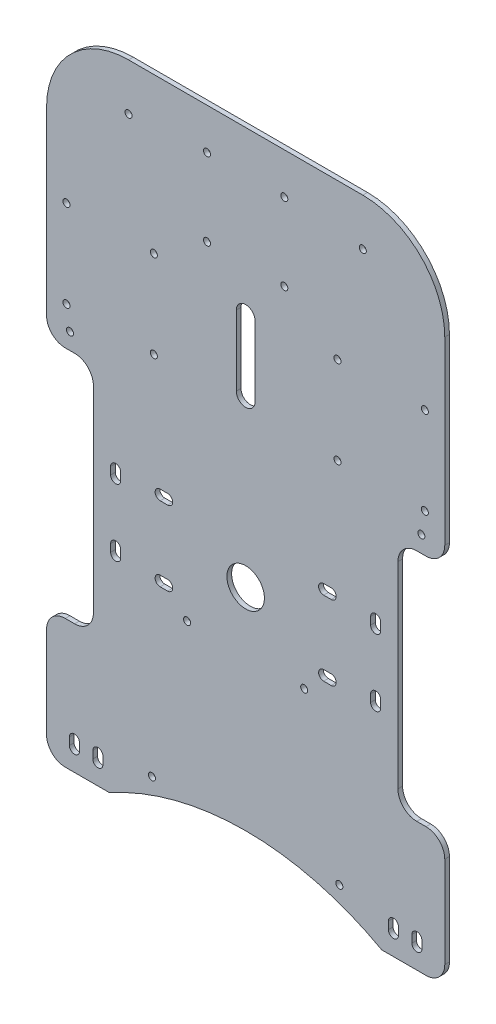
SolidWorks part; units mm, degrees
ref_plane "Front Plane" through (0, 0, 0) normal (0, 0, 1) x (1, 0, 0)
ref_plane "Top Plane" through (0, 0, 0) normal (0, 1, 0) x (1, 0, 0)
ref_plane "Right Plane" through (0, 0, 0) normal (1, 0, 0) x (0, 0, -1)
sketch "Sketch1" plane through (0, 0, 0) normal (0, 0, 1) x (1, 0, 0)
  line L0 (0, 234.6428) -> (0, -211.6883) construction
  line L1 (-148.3119, 0) -> (158.122, 0) construction
  line L2 (85, 170) -> (-85, 170)
  line L3 (-85, 170) -> (-85, 50)
  line L4 (-85, 50) -> (-65, 50)
  line L5 (-65, 50) -> (-65, -50)
  line L6 (-65, -50) -> (-85, -50)
  line L7 (-85, -50) -> (-85, -105)
  line L8 (-85, -105) -> (-58.0948, -105)
  line L9 (85, -50) -> (85, -105)
  line L10 (65, -50) -> (85, -50)
  line L11 (65, 50) -> (65, -50)
  line L12 (85, 50) -> (65, 50)
  line L13 (85, 170) -> (85, 50)
  line L14 (-183.5211, -105) -> (209.6702, -105) construction
  line L15 (-183.5211, -210) -> (209.6702, -210) construction
  line L16 (58.0948, -105) -> (85, -105)
  arc A0 (58.0948, -105) -> (-58.0948, -105) centre (0, -210) ccw
  circle A1 centre (0, 0) radius 8
  point P15 (0, -124.5914)
  point P20 (0, 170)
  dimension "D8" = 120
  dimension "D9" = 16
  dimension "D1" = 100
  dimension "D2" = 50
  dimension "D3" = 20
  dimension "D4" = 120
  dimension "D5" = 55
  dimension "D6" = 85
  dimension "D10" = 85
  dimension "D7" = 105
extrude "Boss-Extrude1" add sketch "Sketch1" along normal blind 2
fillet "Fillet3" radius 35 2 edges at (-85, 170, 1) (85, 170, 1)
fillet "Fillet4" radius 8 5 edges at (-65, -50, 1) (-85, -50, 1) (-85, -105, 1) (-85, 50, 1) (-65, 50, 1)
fillet "Fillet5" radius 8 5 edges at (65, -50, 1) (85, -50, 1) (85, -105, 1) (65, 50, 1) (85, 50, 1)
sketch "Sketch6" plane through (0, 0, 2) normal (0, 0, 1) x (1, 0, 0)
  line L0 (0, 177.7315) -> (0, -125.1538) construction
  line L1 (-144.5008, 0) -> (190.5364, 0) construction
  line L2 (-85, 180.289) -> (-85, -129.9035) construction
  line L3 (-78, 180.289) -> (-78, -129.9035) construction
  line L4 (-144.5008, 50) -> (190.5364, 50) construction
  line L5 (-144.5008, 65) -> (190.5364, 65) construction
  line L6 (-76.5, 180.289) -> (-76.5, -129.9035) construction
  line L7 (-144.5008, 66.5) -> (190.5364, 66.5) construction
  line L8 (-144.5008, 103.8) -> (190.5364, 103.8) construction
  line L9 (-39.2, 180.289) -> (-39.2, -129.9035) construction
  circle A0 centre (-76.5, 66.5) radius 1.5
  circle A1 centre (-76.5, 103.8) radius 1.5
  circle A2 centre (-39.2, 103.8) radius 1.5
  circle A3 centre (-39.2, 66.5) radius 1.5
  circle A4 centre (76.5, 66.5) radius 1.5
  circle A5 centre (76.5, 103.8) radius 1.5
  circle A6 centre (39.2, 103.8) radius 1.5
  circle A7 centre (39.2, 66.5) radius 1.5
  dimension "D7" = 37.3
  dimension "D1" = 7
  dimension "D2" = 50
  dimension "D3" = 15
  dimension "D4" = 1.5
  dimension "D5" = 1.5
  dimension "D6" = 37.3
extrude "Cut-Extrude1" cut sketch "Sketch6" against normal blind 2
sketch "Sketch8" plane through (0, 0, 0) normal (0, 0, -1) x (-1, 0, 0)
  line L0 (0, 179.0295) -> (0, -122.4445) construction
  line L1 (-76.5, 66.5) -> (-76.5, 103.8) construction
  line L2 (-97.6433, 85.5254) -> (107.9764, 85.5254) construction
  line L3 (0, 70.5254) -> (0, 100.5254) construction
  line L4 (-4, 70.5254) -> (-4, 100.5254)
  line L5 (4, 70.5254) -> (4, 100.5254)
  line L6 (-133.0869, 0) -> (148.961, 0) construction
  line L8 (-133.0869, -20.65) -> (148.961, -20.65) construction
  line L9 (-133.0869, 20.65) -> (148.961, 20.65) construction
  line L12 (-30, -42) -> (-30, 42)
  line L13 (-30, -42) -> (-30, 42) construction
  line L14 (-36.5, -42) -> (-36.5, 42) construction
  line L15 (-55.5, -42) -> (-55.5, 42)
  line L16 (-55.5, -42) -> (-55.5, 42) construction
  line L17 (-133.0869, -12.7) -> (148.961, -12.7) construction
  line L18 (-133.0869, 12.7) -> (148.961, 12.7) construction
  line L19 (-133.0869, 15.9) -> (148.961, 15.9) construction
  line L20 (-133.0869, -15.9) -> (148.961, -15.9) construction
  line L21 (-33.3, -42) -> (-33.3, 42) construction
  line L22 (-55.5, 15.9) -> (-55.5, 12.7) construction
  line L23 (-53.35, 15.9) -> (-53.35, 12.7)
  line L24 (-57.65, 15.9) -> (-57.65, 12.7)
  line L25 (-55.5, -15.9) -> (-55.5, -12.7) construction
  line L26 (-53.35, -15.9) -> (-53.35, -12.7)
  line L27 (-57.65, -15.9) -> (-57.65, -12.7)
  line L28 (-33.3, 15.9) -> (-36.5, 15.9) construction
  line L29 (-33.3, 13.75) -> (-36.5, 13.75)
  line L30 (-33.3, 18.05) -> (-36.5, 18.05)
  line L31 (-33.3, -15.9) -> (-36.5, -15.9) construction
  line L32 (-33.3, -13.75) -> (-36.5, -13.75)
  line L33 (-33.3, -18.05) -> (-36.5, -18.05)
  line L34 (33.3, -15.9) -> (36.5, -15.9) construction
  line L35 (33.3, -13.75) -> (36.5, -13.75)
  line L36 (33.3, -18.05) -> (36.5, -18.05)
  line L37 (33.3, 15.9) -> (36.5, 15.9) construction
  line L38 (33.3, 13.75) -> (36.5, 13.75)
  line L39 (33.3, 18.05) -> (36.5, 18.05)
  line L40 (55.5, 15.9) -> (55.5, 12.7) construction
  line L41 (53.35, 15.9) -> (53.35, 12.7)
  line L42 (57.65, 15.9) -> (57.65, 12.7)
  line L43 (55.5, -15.9) -> (55.5, -12.7) construction
  line L44 (53.35, -15.9) -> (53.35, -12.7)
  line L45 (57.65, -15.9) -> (57.65, -12.7)
  arc A0 (-4, 70.5254) -> (4, 70.5254) centre (0, 70.5254) ccw
  arc A1 (4, 100.5254) -> (-4, 100.5254) centre (0, 100.5254) ccw
  arc A2 (-53.35, 15.9) -> (-57.65, 15.9) centre (-55.5, 15.9) ccw
  arc A3 (-57.65, 12.7) -> (-53.35, 12.7) centre (-55.5, 12.7) ccw
  arc A4 (-53.35, -15.9) -> (-57.65, -15.9) centre (-55.5, -15.9) cw
  arc A5 (-57.65, -12.7) -> (-53.35, -12.7) centre (-55.5, -12.7) cw
  arc A6 (-33.3, 13.75) -> (-33.3, 18.05) centre (-33.3, 15.9) ccw
  arc A7 (-36.5, 18.05) -> (-36.5, 13.75) centre (-36.5, 15.9) ccw
  arc A8 (-33.3, -13.75) -> (-33.3, -18.05) centre (-33.3, -15.9) cw
  arc A9 (-36.5, -18.05) -> (-36.5, -13.75) centre (-36.5, -15.9) cw
  arc A10 (33.3, -13.75) -> (33.3, -18.05) centre (33.3, -15.9) ccw
  arc A11 (36.5, -18.05) -> (36.5, -13.75) centre (36.5, -15.9) ccw
  arc A12 (33.3, 13.75) -> (33.3, 18.05) centre (33.3, 15.9) cw
  arc A13 (36.5, 18.05) -> (36.5, 13.75) centre (36.5, 15.9) cw
  arc A14 (53.35, 15.9) -> (57.65, 15.9) centre (55.5, 15.9) cw
  arc A15 (57.65, 12.7) -> (53.35, 12.7) centre (55.5, 12.7) cw
  arc A16 (53.35, -15.9) -> (57.65, -15.9) centre (55.5, -15.9) ccw
  arc A17 (57.65, -12.7) -> (53.35, -12.7) centre (55.5, -12.7) ccw
  point P9 (0, 85.5254)
  point P40 (-55.5, 14.3)
  point P47 (-55.5, -14.3)
  point P54 (-34.9, 15.9)
  point P61 (-34.9, -15.9)
  point P68 (34.9, -15.9)
  point P75 (34.9, 15.9)
  point P82 (55.5, 14.3)
  point P89 (55.5, -14.3)
  dimension "D1" = 8
  dimension "D2" = 30
  dimension "D12" = 2.15
  dimension "D13" = 2.15
  dimension "D3" = 20.65
  dimension "D4" = 20.65
  dimension "D5" = 35
  dimension "D6" = 9.5
  dimension "D7" = 19
  dimension "D8" = 12.7
  dimension "D9" = 12.7
  dimension "D10" = 3.2
  dimension "D11" = 3.2
extrude "Cut-Extrude2" cut sketch "Sketch8" against normal blind 10
sketch "Sketch9" plane through (0, 0, 2) normal (0, 0, 1) x (1, 0, 0)
  line L0 (-85, -58) -> (-85, -97) construction
  line L1 (-58.0948, -102) -> (-58.0948, -87) construction
  line L2 (-78.0948, -102) -> (-78.0948, -87) construction
  line L3 (-109.7746, -105) -> (-30.809, -105) construction
  line L4 (-109.7746, -102) -> (-30.809, -102) construction
  line L5 (-109.7746, -87) -> (-30.809, -87) construction
  line L6 (-78.0948, -132.8719) -> (-78.0948, -87) construction
  line L7 (-58.0948, -132.8719) -> (-58.0948, -87) construction
  line L8 (-78.0948, -94.5) -> (-58.0948, -94.5) construction
  line L9 (-68.0948, -87) -> (-68.0948, -102) construction
  line L10 (-73.0948, -87) -> (-73.0948, -102) construction
  line L11 (-63.0948, -87) -> (-63.0948, -102) construction
  line L12 (-78.0948, -96.1) -> (-58.0948, -96.1) construction
  line L13 (-78.0948, -92.9) -> (-58.0948, -92.9) construction
  line L14 (-73.0948, -92.9) -> (-73.0948, -96.1) construction
  line L15 (-70.9448, -92.9) -> (-70.9448, -96.1)
  line L16 (-75.2448, -92.9) -> (-75.2448, -96.1)
  line L17 (-63.0948, -92.9) -> (-63.0948, -96.1) construction
  line L18 (-65.2448, -92.9) -> (-65.2448, -96.1)
  line L19 (-60.9448, -92.9) -> (-60.9448, -96.1)
  line L20 (0, -132.6112) -> (0, -29.5996) construction
  line L21 (63.0948, -92.9) -> (63.0948, -96.1) construction
  line L22 (65.2448, -92.9) -> (65.2448, -96.1)
  line L23 (60.9448, -92.9) -> (60.9448, -96.1)
  line L24 (73.0948, -92.9) -> (73.0948, -96.1) construction
  line L25 (70.9448, -92.9) -> (70.9448, -96.1)
  line L26 (75.2448, -92.9) -> (75.2448, -96.1)
  arc A1 (-70.9448, -92.9) -> (-75.2448, -92.9) centre (-73.0948, -92.9) ccw
  arc A2 (-75.2448, -96.1) -> (-70.9448, -96.1) centre (-73.0948, -96.1) ccw
  arc A3 (-65.2448, -92.9) -> (-60.9448, -92.9) centre (-63.0948, -92.9) cw
  arc A4 (-60.9448, -96.1) -> (-65.2448, -96.1) centre (-63.0948, -96.1) cw
  arc A5 (65.2448, -92.9) -> (60.9448, -92.9) centre (63.0948, -92.9) ccw
  arc A6 (60.9448, -96.1) -> (65.2448, -96.1) centre (63.0948, -96.1) ccw
  arc A7 (70.9448, -92.9) -> (75.2448, -92.9) centre (73.0948, -92.9) cw
  arc A8 (75.2448, -96.1) -> (70.9448, -96.1) centre (73.0948, -96.1) cw
  point P30 (-73.0948, -94.5)
  point P37 (-63.0948, -94.5)
  point P47 (63.0948, -94.5)
  point P54 (73.0948, -94.5)
  dimension "D1" = 26.9052
  dimension "D9" = 2.15
  dimension "D2" = 20
  dimension "D3" = 3
  dimension "D4" = 15
  dimension "D5" = 5
  dimension "D6" = 5
  dimension "D7" = 1.6
  dimension "D8" = 1.6
extrude "Cut-Extrude3" cut sketch "Sketch9" against normal blind 10
sketch "Sketch10" plane through (0, 0, 2) normal (0, 0, 1) x (1, 0, 0)
  line L0 (-75, 50) -> (-95.2715, 50) construction
  line L1 (-77, 50) -> (-73, 50) construction
  line L2 (0, 209.9299) -> (0, -118.8515) construction
  line L3 (50, 150) -> (-50, 150)
  line L4 (50, 150) -> (-59.9342, 150) construction
  line L5 (-50, 209.9299) -> (-50, -118.8515) construction
  line L6 (-75, 57) -> (-95.2715, 57) construction
  line L8 (-75, 135) -> (-75, 58)
  line L9 (-75, 135) -> (-75, 44.6632) construction
  circle A0 centre (-50, 150) radius 1.5
  circle A1 centre (50, 150) radius 1.5
  circle A2 centre (-75, 57) radius 1.5
  circle A3 centre (75, 57) radius 1.5
  dimension "D3" = 3
  dimension "D5" = 3
  dimension "D1" = 20
  dimension "D2" = 50
  dimension "D4" = 10
extrude "Cut-Extrude4" cut sketch "Sketch10" against normal blind 10
sketch "Sketch11" plane through (0, 0, 2) normal (0, 0, 1) x (1, 0, 0)
  line L0 (-113.8571, -105) -> (102.2823, -105) construction
  line L1 (-113.8571, -10) -> (102.2823, -10) construction
  line L2 (-113.8571, -90) -> (102.2823, -90) construction
  line L3 (0, -122.9754) -> (0, 46.6884) construction
  line L4 (40, -122.9754) -> (40, 46.6884) construction
  line L5 (-40, -122.9754) -> (-40, 46.6884) construction
  line L6 (-113.8571, -25) -> (102.2823, -25) construction
  line L7 (30, -122.9754) -> (30, 46.6884) construction
  line L8 (-25, -122.9754) -> (-25, 46.6884) construction
  circle A0 centre (-40, -90) radius 1.5
  circle A1 centre (40, -90) radius 1.5
  circle A2 centre (-25, -25) radius 1.5
  circle A3 centre (25, -25) radius 1.5
  dimension "D5" = 3
  dimension "D9" = 3
  dimension "D1" = 95
  dimension "D2" = 15
  dimension "D3" = 40
  dimension "D4" = 40
  dimension "D6" = 15
  dimension "D7" = 30
  dimension "D8" = 25
extrude "Cut-Extrude5" cut sketch "Sketch11" against normal blind 10
sketch "Sketch12" plane through (0, 0, 2) normal (0, 0, 1) x (1, 0, 0)
  line L0 (0, 26.5762) -> (0, 202.7055) construction
  line L1 (50, 170) -> (-50, 170) construction
  line L2 (-43.9552, 118) -> (48.2873, 118) construction
  line L3 (50, 107) -> (-50, 107) construction
  line L4 (50, 165) -> (-50, 165)
  line L5 (50, 165) -> (-50, 165) construction
  line L7 (-43.9552, 136) -> (48.2873, 136) construction
  line L8 (-43.9552, 154) -> (48.2873, 154) construction
  line L10 (-43.9552, 119.5) -> (48.2873, 119.5) construction
  line L11 (16.5, 26.5762) -> (16.5, 202.7055) construction
  line L12 (-16.5, 26.5762) -> (-16.5, 202.7055) construction
  arc A0 (4, 100.5254) -> (-4, 100.5254) centre (0, 100.5254) ccw construction
  circle A1 centre (-16.5, 119.5) radius 1.5
  circle A2 centre (-16.5, 152.5) radius 1.5
  circle A3 centre (16.5, 119.5) radius 1.5
  circle A4 centre (16.5, 152.5) radius 1.5
  dimension "D1" = 69.4746
  dimension "D6" = 16.5
  dimension "D7" = 1.5
  dimension "D8" = 16.5
  dimension "D2" = 5
  dimension "D3" = 58
  dimension "D4" = 18
  dimension "D5" = 18
extrude "Cut-Extrude6" cut sketch "Sketch12" against normal blind 20
